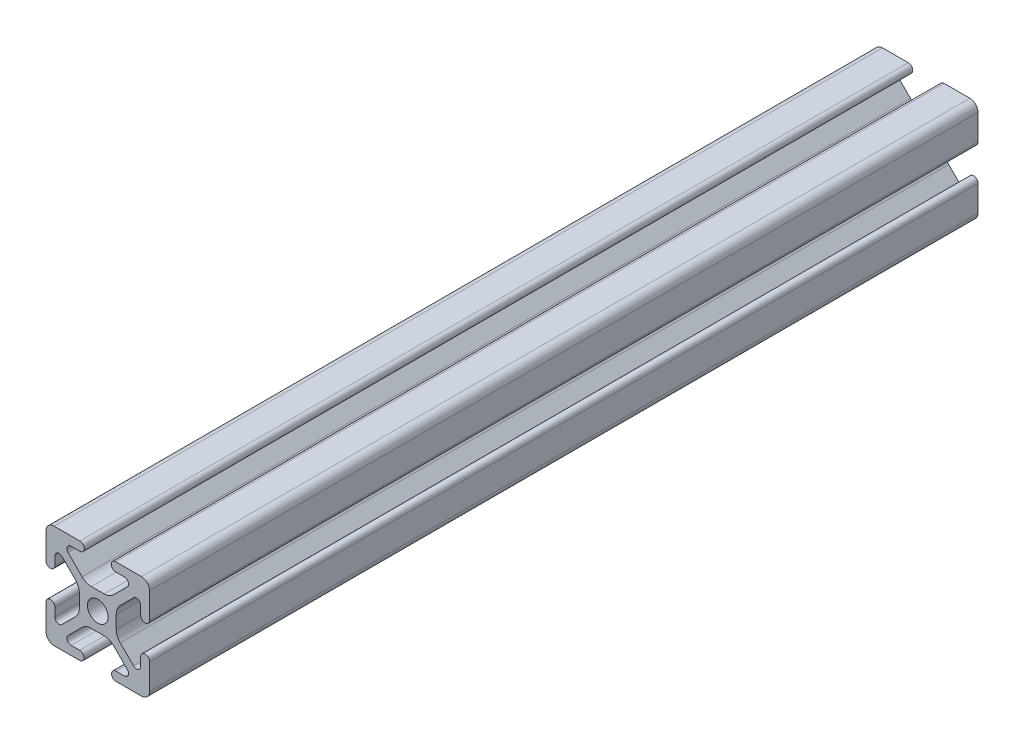
SolidWorks part; units mm, degrees
ref_plane "Front Plane" through (0, 0, 0) normal (0, 0, 1) x (1, 0, 0)
ref_plane "Top Plane" through (0, 0, 0) normal (0, 1, 0) x (1, 0, 0)
ref_plane "Right Plane" through (0, 0, 0) normal (1, 0, 0) x (0, 0, -1)
ref_plane "Plane1" through (0, 0, -4000) normal (0, 0, -1) x (-1, 0, 0)
sketch "Sketch1" plane through (0, 0, -4000) normal (0, 0, -1) x (-1, 0, 0)
  line L0 (12.5, 4.32) -> (12.5, 10.5371)
  line L1 (10.5371, 12.5) -> (4.32, 12.5)
  line L2 (4.32, 10.36) -> (6.42, 10.36)
  line L3 (7.1337, 8.6353) -> (3.7953, 5.3018)
  line L4 (1.5554, 4.375) -> (-1.5554, 4.375)
  line L5 (-3.7953, 5.3018) -> (-7.1337, 8.6353)
  line L6 (-6.42, 10.36) -> (-4.32, 10.36)
  line L7 (-4.32, 12.5) -> (-10.5371, 12.5)
  line L8 (-12.5, 10.5371) -> (-12.5, 4.32)
  line L9 (-10.36, 4.32) -> (-10.36, 6.3969)
  line L10 (-8.6363, 7.1116) -> (-5.4322, 3.9121)
  line L11 (-4.455, 1.5554) -> (-4.455, -1.5554)
  line L12 (-5.4322, -3.9121) -> (-8.6363, -7.1116)
  line L13 (-10.36, -6.3969) -> (-10.36, -4.32)
  line L14 (-12.5, -4.32) -> (-12.5, -10.5371)
  line L15 (-10.5371, -12.5) -> (-4.3879, -12.5)
  line L16 (-4.3879, -10.36) -> (-6.42, -10.36)
  line L17 (-7.1337, -8.6353) -> (-3.7953, -5.3018)
  line L18 (-1.5554, -4.375) -> (1.5554, -4.375)
  line L19 (3.7953, -5.3018) -> (7.1337, -8.6353)
  line L20 (6.42, -10.36) -> (4.3879, -10.36)
  line L21 (4.3879, -12.5) -> (10.5371, -12.5)
  line L22 (12.5, -10.5371) -> (12.5, -4.32)
  line L23 (10.36, -4.32) -> (10.36, -6.3969)
  line L24 (8.6363, -7.1116) -> (5.4322, -3.9121)
  line L25 (4.455, -1.5554) -> (4.455, 1.5554)
  line L26 (5.4322, 3.9121) -> (8.6363, 7.1116)
  line L27 (10.36, 6.3969) -> (10.36, 4.32)
  circle A0 centre (0, 0) radius 2.5
  arc A1 (12.5, 10.5371) -> (10.5371, 12.5) centre (10.5371, 10.5371) ccw
  arc A2 (4.32, 12.5) -> (4.32, 10.36) centre (4.32, 11.43) ccw
  arc A3 (6.42, 10.36) -> (7.1337, 8.6353) centre (6.42, 9.35) cw
  arc A4 (3.7953, 5.3018) -> (1.5554, 4.375) centre (1.5554, 7.545) cw
  arc A5 (-1.5554, 4.375) -> (-3.7953, 5.3018) centre (-1.5554, 7.545) cw
  arc A6 (-7.1337, 8.6353) -> (-6.42, 10.36) centre (-6.42, 9.35) cw
  arc A7 (-4.32, 10.36) -> (-4.32, 12.5) centre (-4.32, 11.43) ccw
  arc A8 (-10.5371, 12.5) -> (-12.5, 10.5371) centre (-10.5371, 10.5371) ccw
  arc A9 (-12.5, 4.32) -> (-10.36, 4.32) centre (-11.43, 4.32) ccw
  arc A10 (-10.36, 6.3969) -> (-8.6363, 7.1116) centre (-9.35, 6.3969) cw
  arc A11 (-5.4322, 3.9121) -> (-4.455, 1.5554) centre (-7.7855, 1.5554) cw
  arc A12 (-4.455, -1.5554) -> (-5.4322, -3.9121) centre (-7.7855, -1.5554) cw
  arc A13 (-8.6363, -7.1116) -> (-10.36, -6.3969) centre (-9.35, -6.3969) cw
  arc A14 (-10.36, -4.32) -> (-12.5, -4.32) centre (-11.43, -4.32) ccw
  arc A15 (-12.5, -10.5371) -> (-10.5371, -12.5) centre (-10.5371, -10.5371) ccw
  arc A16 (-4.3879, -12.5) -> (-4.3879, -10.36) centre (-4.3879, -11.43) ccw
  arc A17 (-6.42, -10.36) -> (-7.1337, -8.6353) centre (-6.42, -9.35) cw
  arc A18 (-3.7953, -5.3018) -> (-1.5554, -4.375) centre (-1.5554, -7.545) cw
  arc A19 (1.5554, -4.375) -> (3.7953, -5.3018) centre (1.5554, -7.545) cw
  arc A20 (7.1337, -8.6353) -> (6.42, -10.36) centre (6.42, -9.35) cw
  arc A21 (4.3879, -10.36) -> (4.3879, -12.5) centre (4.3879, -11.43) ccw
  arc A22 (10.5371, -12.5) -> (12.5, -10.5371) centre (10.5371, -10.5371) ccw
  arc A23 (12.5, -4.32) -> (10.36, -4.32) centre (11.43, -4.32) ccw
  arc A24 (10.36, -6.3969) -> (8.6363, -7.1116) centre (9.35, -6.3969) cw
  arc A25 (5.4322, -3.9121) -> (4.455, -1.5554) centre (7.7855, -1.5554) cw
  arc A26 (4.455, 1.5554) -> (5.4322, 3.9121) centre (7.7855, 1.5554) cw
  arc A27 (8.6363, 7.1116) -> (10.36, 6.3969) centre (9.35, 6.3969) cw
  arc A28 (10.36, 4.32) -> (12.5, 4.32) centre (11.43, 4.32) ccw
extrude "Boss-Extrude1" add sketch "Sketch1" against normal blind 200
